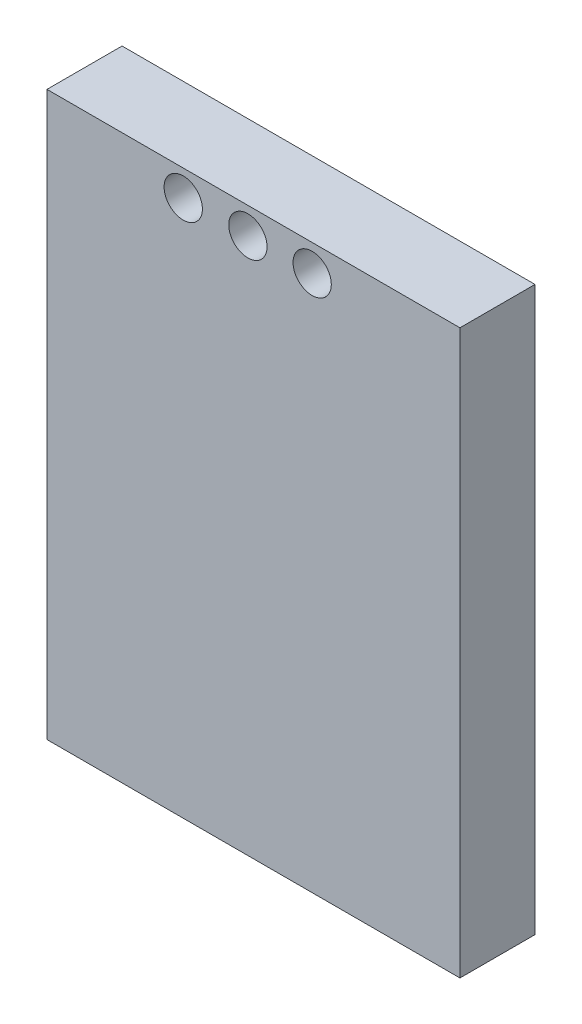
SolidWorks part; units mm, degrees
ref_plane "前视基准面" through (0, 0, 0) normal (0, 0, 1) x (1, 0, 0)
ref_plane "上视基准面" through (0, 0, 0) normal (0, 1, 0) x (1, 0, 0)
ref_plane "右视基准面" through (0, 0, 0) normal (1, 0, 0) x (0, 0, -1)
sketch "草图1" plane through (0, 0, 0) normal (0, 0, 1) x (1, 0, 0)
  line L1 (-5.5, 7.5) -> (5.5, 7.5)
  line L2 (-5.5, 7.5) -> (-5.5, -7.5)
  line L3 (-5.5, -7.5) -> (5.5, -7.5)
  line L4 (5.5, 7.5) -> (5.5, -7.5)
  line L5 (-5.5, 7.5) -> (5.5, -7.5) construction
  line L6 (-5.5, -7.5) -> (5.5, 7.5) construction
  point P0 (0, 0)
  dimension "D1" = 11
  dimension "D2" = 15
extrude "凸台-拉伸1" add sketch "草图1" along normal blind 2
sketch "草图2" plane through (0, 0, 2) normal (0, 0, 1) x (1, 0, 0)
  circle A0 centre (-1.8706, 6.8083) radius 0.51
  circle A1 centre (-0.1478, 6.797) radius 0.51
  circle A2 centre (1.5636, 6.7857) radius 0.51
extrude "切除-拉伸1" cut sketch "草图2" against normal through all
sketch "草图3" plane through (0, 0, 2) normal (0, 0, 1) x (1, 0, 0)
  circle A0 centre (0, 0) radius 4.5652
  circle A1 centre (0, 0) radius 3.7193
  circle A2 centre (0, 0) radius 3.0996
  circle A3 centre (0, 0) radius 2.3408
